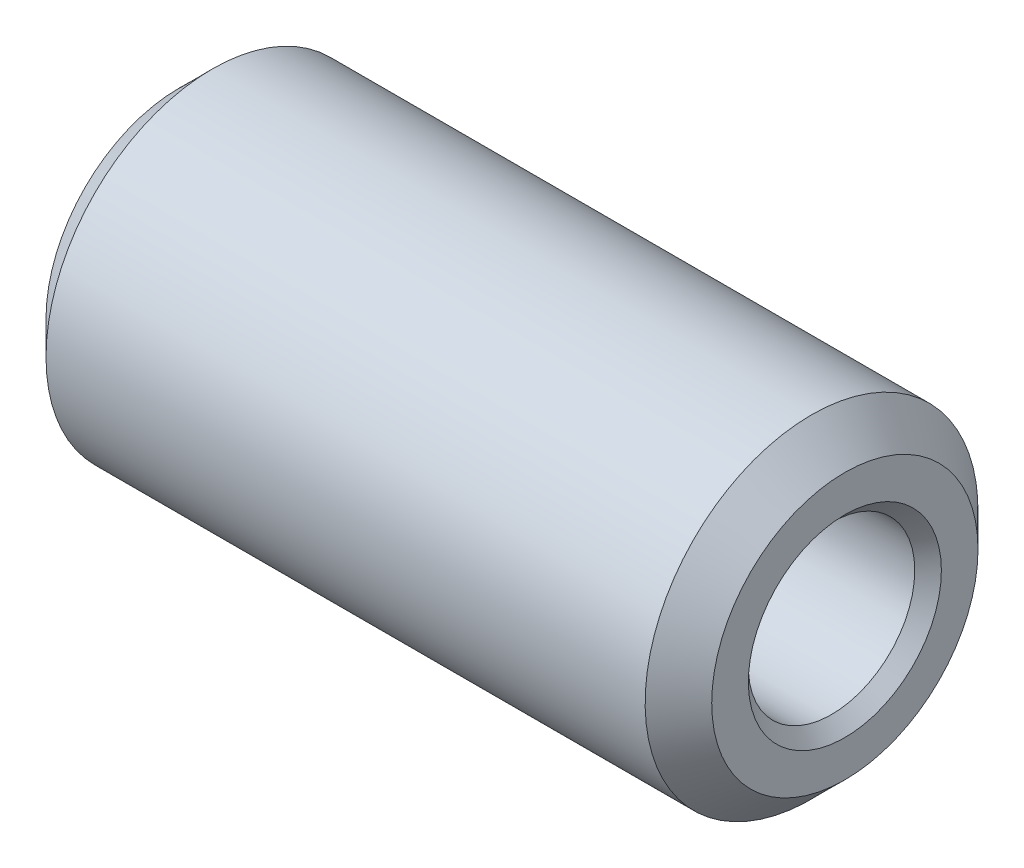
SolidWorks part; units mm, degrees
ref_plane "Спереди" through (0, 0, 0) normal (0, 0, 1) x (1, 0, 0)
ref_plane "Сверху" through (0, 0, 0) normal (0, 1, 0) x (1, 0, 0)
ref_plane "Справа" through (0, 0, 0) normal (1, 0, 0) x (0, 0, -1)
sketch "Эскиз1" plane through (0, 0, 0) normal (0, 0, 1) x (1, 0, 0)
  line L0 (0, 0) -> (0, 2.5)
  line L1 (0, 2.5) -> (10, 2.5)
  line L2 (10, 2.5) -> (10, 0)
  line L3 (10, 0) -> (0, 0)
  dimension "D1" = 10
  dimension "D2" = 2.5
revolve "Повернуть1" add sketch "Эскиз1" angle 360 about L3
hole_wizard "Отверстие обработанное метчиком M31" positions "Эскиз3" profile "Эскиз4" tap size "M3" standard "ISO" end condition through all
sketch "Эскиз3" plane through (10, 0, 0) normal (1, 0, 0) x (0, 0, -1)
  point P0 (0, 0)
sketch "Эскиз4" plane through (10, 0, 0) normal (0, 1, 0) x (0, 0, -1)
  line L0 (0, 0) -> (0, 10)
  line L1 (0, 10) -> (1.25, 10)
  line L2 (1.25, 10) -> (1.25, 0)
  line L5 (1.25, 0) -> (0, 0)
  line L11 (0, -6.35) -> (0, 107.95) construction
  dimension "Диаметр проходного сверла" = 2.5
  dimension "Глубина проходного сверла" = 10
cosmetic thread "Отверстие резьбы1" parameters "D2"=3
chamfer "Фаска1" distance 0.2 angle 45 2 edges at (0, 0, -1.25) (10, 0, -1.25)
chamfer "Фаска2" distance 0.5 angle 45 2 edges at (0, 2.5, 0) (10, 2.5, 0)
